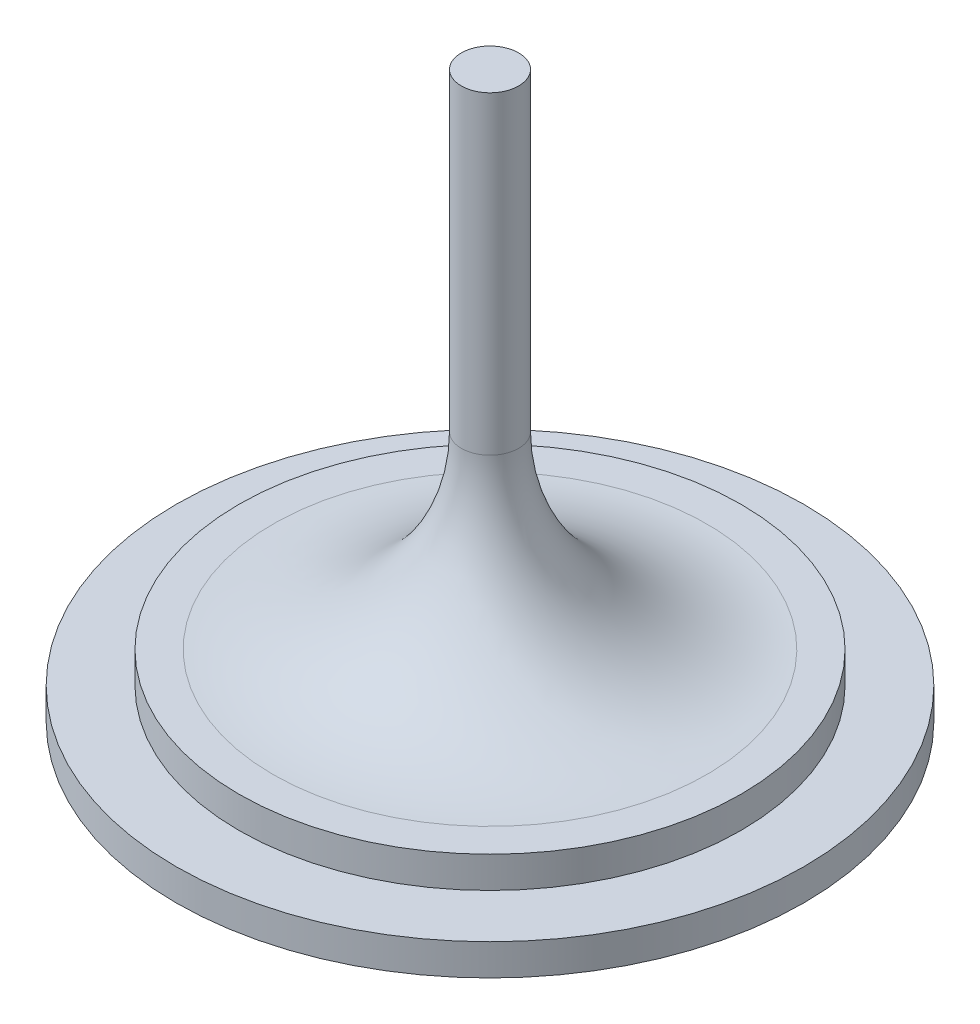
SolidWorks part; units mm, degrees
ref_plane "Front Plane" through (0, 0, 0) normal (0, 0, 1) x (1, 0, 0)
ref_plane "Top Plane" through (0, 0, 0) normal (0, 1, 0) x (1, 0, 0)
ref_plane "Right Plane" through (0, 0, 0) normal (1, 0, 0) x (0, 0, -1)
sketch "Sketch1" plane through (0, 0, 0) normal (0, 0, 1) x (1, 0, 0)
  line L0 (0, 0) -> (31.75, 0)
  line L2 (21.95, 6.35) -> (25.4, 6.35)
  line L3 (2.9, 25.4) -> (2.9, 57.15)
  line L4 (2.9, 57.15) -> (0, 57.15)
  line L5 (0, 57.15) -> (0, 0)
  line L6 (0, 0) -> (0, -24882.6578) construction
  line L7 (25.4, 3.175) -> (31.75, 3.175)
  line L8 (31.75, 3.175) -> (31.75, 0)
  line L9 (25.4, 3.175) -> (25.4, 6.35)
  arc A0 (21.95, 6.35) -> (2.9, 25.4) centre (21.95, 25.4) cw
  dimension "D1" = 3.175
  dimension "D5" = 19.05
  dimension "D2" = 3.175
  dimension "D3" = 5.8
  dimension "D4" = 57.15
  dimension "D6" = 6.35
  dimension "D7" = 63.5
revolve "Revolve1" add sketch "Sketch1" angle 360 about L6
